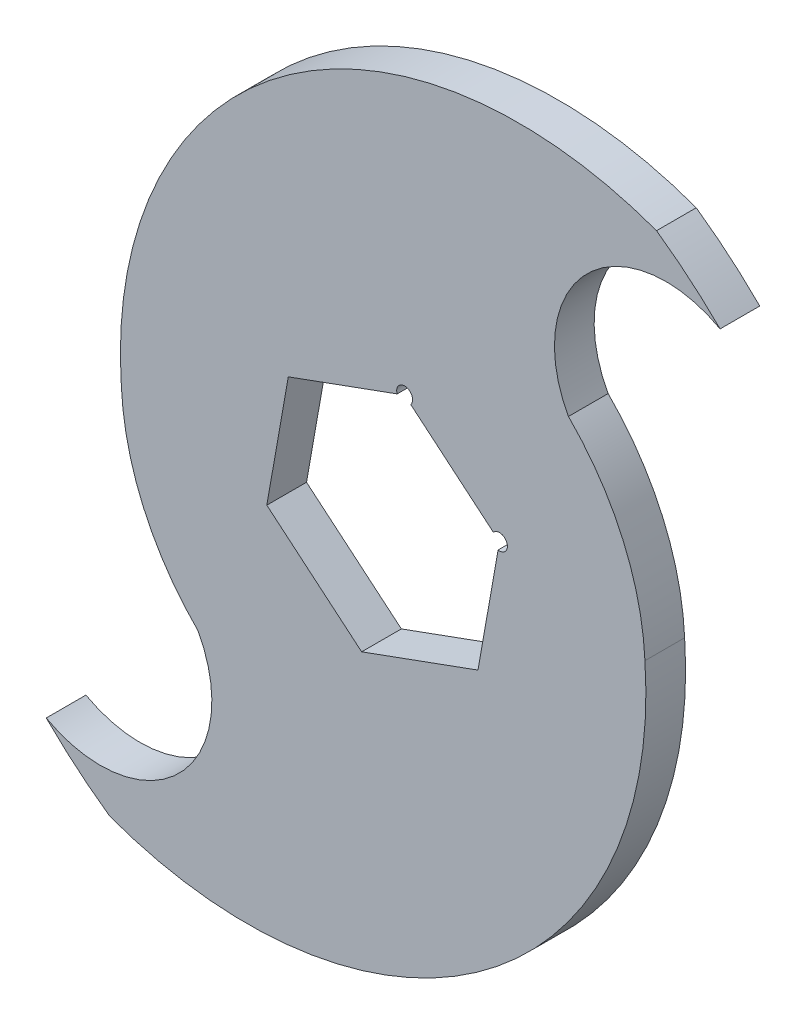
SolidWorks part; units mm, degrees
ref_plane "Front" through (0, 0, 0) normal (0, 0, 1) x (1, 0, 0)
ref_plane "Top" through (0, 0, 0) normal (0, 1, 0) x (1, 0, 0)
ref_plane "Right" through (0, 0, 0) normal (1, 0, 0) x (0, 0, -1)
sketch "Model" plane through (0, 0, 0) normal (0, 0, 1) x (1, 0, 0)
  line L0 (697.3559, 72.048) -> (686.9465, 80.7824)
  line L1 (685.2408, 81.0832) -> (671.5321, 76.0937)
  line L2 (671.5321, 76.0937) -> (668.8252, 60.742)
  line L3 (668.8252, 60.742) -> (680.7667, 50.722)
  line L4 (680.7667, 50.722) -> (695.415, 56.0535)
  line L5 (695.415, 56.0535) -> (697.9483, 70.4204)
  arc A0 (686.9465, 80.7824) -> (685.2408, 81.0832) centre (686.1805, 81.4252) ccw
  arc A1 (697.9483, 70.4204) -> (697.3559, 72.048) centre (698.122, 71.4052) ccw
  arc A2 (717.9, 115.2144) -> (650.5085, 64.5572) centre (700.6, 68.0738) ccw
  arc A3 (650.5085, 64.5572) -> (660.1391, 42.7391) centre (683.4736, 66.0736) ccw
  arc A4 (641.0472, 23.6472) -> (660.1391, 42.7391) centre (647.8637, 35.9226) ccw
  arc A5 (641.0472, 23.6472) -> (649.0472, 16.9328) centre (683.4736, 66.0736) ccw
  arc A6 (649.0472, 16.9328) -> (716.4387, 67.59) centre (666.3472, 64.0734) ccw
  arc A7 (716.4387, 67.59) -> (706.8081, 89.4081) centre (683.4736, 66.0736) ccw
  arc A8 (725.9, 108.5) -> (706.8081, 89.4081) centre (719.0835, 96.2246) ccw
  arc A9 (725.9, 108.5) -> (717.9, 115.2144) centre (683.4736, 66.0736) ccw
extrude "Boss-Extrude1" add sketch "Model" along normal mid plane 5
